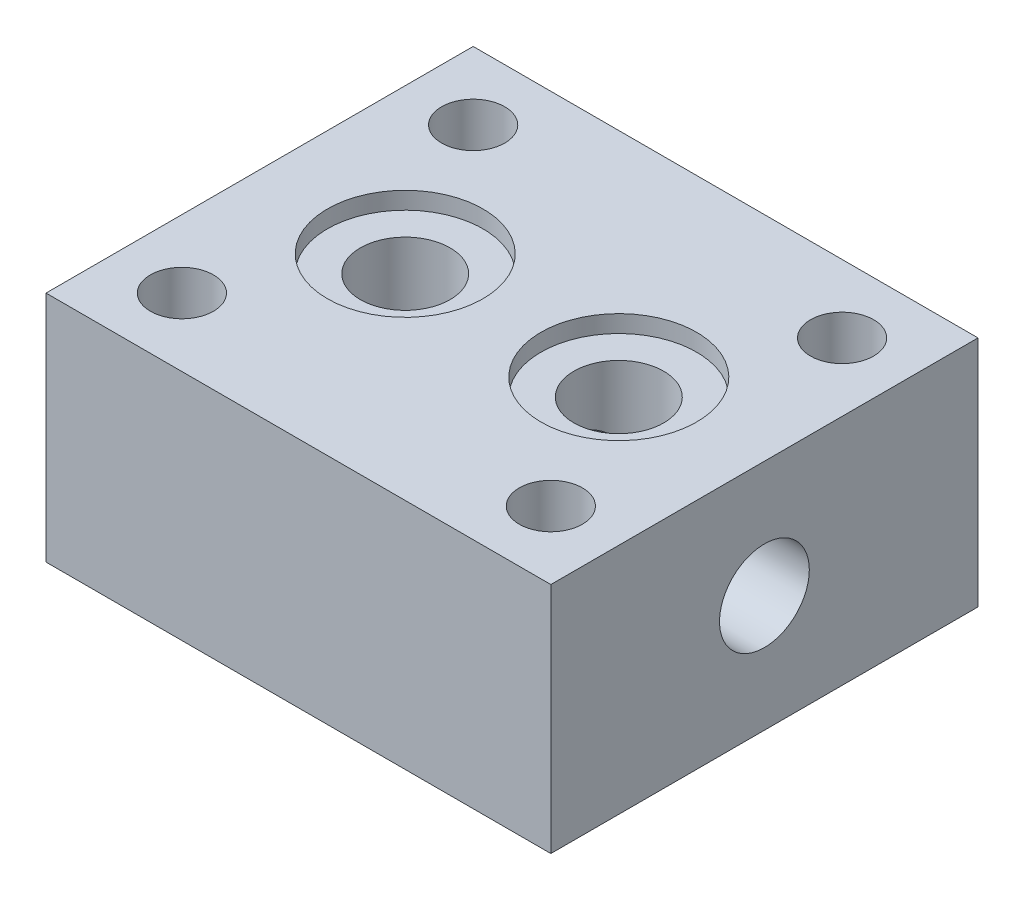
SolidWorks part; units mm, degrees
ref_plane "Front Plane" through (0, 0, 0) normal (0, 0, 1) x (1, 0, 0)
ref_plane "Top Plane" through (0, 0, 0) normal (0, 1, 0) x (1, 0, 0)
ref_plane "Right Plane" through (0, 0, 0) normal (1, 0, 0) x (0, 0, -1)
sketch "Sketch1" plane through (0, 0, 0) normal (0, 1, 0) x (1, 0, 0)
  line L1 (-41.275, -34.925) -> (41.275, -34.925)
  line L2 (-41.275, -34.925) -> (-41.275, 34.925)
  line L3 (-41.275, 34.925) -> (41.275, 34.925)
  line L4 (41.275, -34.925) -> (41.275, 34.925)
  line L5 (-41.275, -34.925) -> (41.275, 34.925) construction
  line L6 (-41.275, 34.925) -> (41.275, -34.925) construction
  point P0 (0, 0)
  dimension "D1" = 41.275
  dimension "D2" = 34.925
extrude "Boss-Extrude1" add sketch "Sketch1" along normal mid plane 38.1
sketch "Sketch2" plane through (0, 0, 0) normal (0, 1, 0) x (1, 0, 0)
  circle A0 centre (-30.1625, -23.8125) radius 5.1594
  circle A1 centre (30.1625, -23.8125) radius 5.1594
  circle A2 centre (-30.1625, 23.8125) radius 5.1594
  circle A3 centre (30.1625, 23.8125) radius 5.1594
  point P8 (0, 0)
  dimension "D1" = 10.3188
  dimension "D2" = 10.3187
  dimension "D3" = 10.3187
  dimension "D4" = 10.3188
  dimension "D5" = 60.325
  dimension "D6" = 47.625
  dimension "D7" = 30.1625
  dimension "D8" = 23.8125
extrude "Cut-Extrude2" cut sketch "Sketch2" against normal through all from offset 19.05
sketch "Sketch3" plane through (0, 0, 0) normal (0, 1, 0) x (1, 0, 0)
  circle A0 centre (-17.4625, 0) radius 7.3422
  circle A1 centre (17.4625, 0) radius 7.3422
  point P4 (0, 0)
  dimension "D1" = 14.6844
  dimension "D2" = 14.6844
  dimension "D3" = 34.925
  dimension "D4" = 17.4625
extrude "Cut-Extrude4" cut sketch "Sketch3" against normal blind 28.575 from offset 19.05
sketch "Sketch4" plane through (0, 0, 0) normal (0, 1, 0) x (1, 0, 0)
  circle A0 centre (-17.4625, 0) radius 12.7254
  circle A1 centre (17.4625, 0) radius 12.7254
  point P4 (0, 0)
  dimension "D1" = 25.4508
  dimension "D2" = 25.4508
  dimension "D3" = 34.925
  dimension "D4" = 17.4625
extrude "Cut-Extrude6" cut sketch "Sketch4" against normal blind 2.8194 from offset 19.05
sketch "Sketch5" plane through (0, 0, 0) normal (1, 0, 0) x (0, 0, -1)
  circle A0 centre (0, 0) radius 7.3422
  point P2 (0, 0)
  dimension "D1" = 14.6844
extrude "Cut-Extrude8" cut sketch "Sketch5" against normal blind 60.325 from offset 41.275
